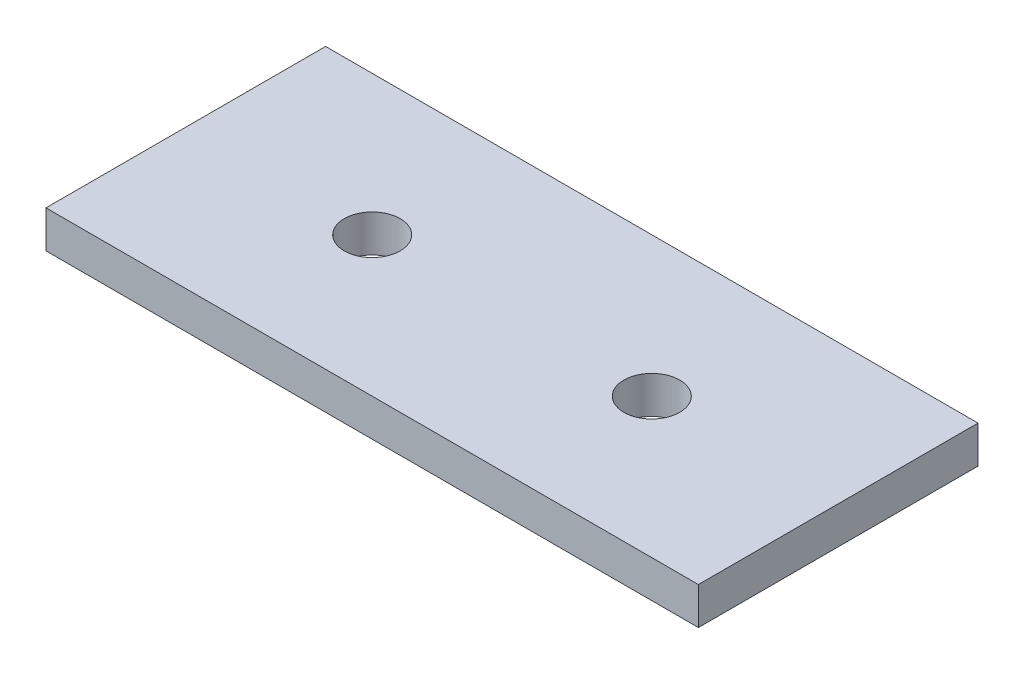
SolidWorks part; units mm, degrees
ref_plane "Front Plane" through (0, 0, 0) normal (0, 0, 1) x (1, 0, 0)
ref_plane "Top Plane" through (0, 0, 0) normal (0, 1, 0) x (1, 0, 0)
ref_plane "Right Plane" through (0, 0, 0) normal (1, 0, 0) x (0, 0, -1)
sketch "Sketch1" plane through (0, 0, 0) normal (0, 1, 0) x (1, 0, 0)
  line L0 (0, 7.5) -> (35, 7.5)
  line L1 (0, 0) -> (35, 0)
  line L2 (0, 0) -> (0, 15)
  line L3 (0, 15) -> (35, 15)
  line L4 (35, 0) -> (35, 15)
  circle A0 centre (10, 7.5) radius 1.5
  circle A1 centre (25, 7.5) radius 1.5
  dimension "D3" = 10
  dimension "D4" = 15
  dimension "D1" = 15
  dimension "D2" = 35
extrude "Boss-Extrude1" add sketch "Sketch1" along normal blind 2 contours A1 L0 A0 L2 L1 L4 | A1 L0 L4 L3 L2 A0
